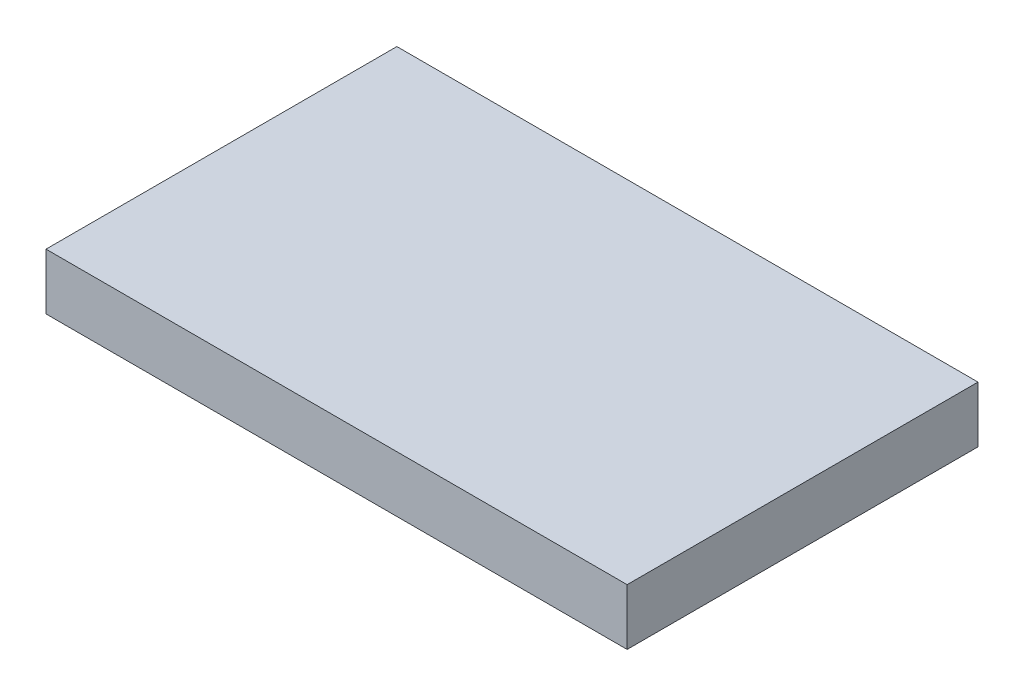
SolidWorks part; units mm, degrees
ref_plane "Front Plane" through (0, 0, 0) normal (0, 0, 1) x (1, 0, 0)
ref_plane "Top Plane" through (0, 0, 0) normal (0, 1, 0) x (1, 0, 0)
ref_plane "Right Plane" through (0, 0, 0) normal (1, 0, 0) x (0, 0, -1)
sketch "Sketch1" plane through (0, 0, 0) normal (0, 1, 0) x (1, 0, 0)
  line L1 (-105.4729, -12.0363) -> (-79.1667, -12.0363)
  line L2 (-105.4729, -12.0363) -> (-105.4729, 3.8467)
  line L3 (-105.4729, 3.8467) -> (-79.1667, 3.8467)
  line L4 (-79.1667, -12.0363) -> (-79.1667, 3.8467)
  line L5 (-105.4729, -12.0363) -> (-79.1667, 3.8467) construction
  line L6 (-105.4729, 3.8467) -> (-79.1667, -12.0363) construction
extrude "Boss-Extrude1" add sketch "Sketch1" along normal blind 2.54
